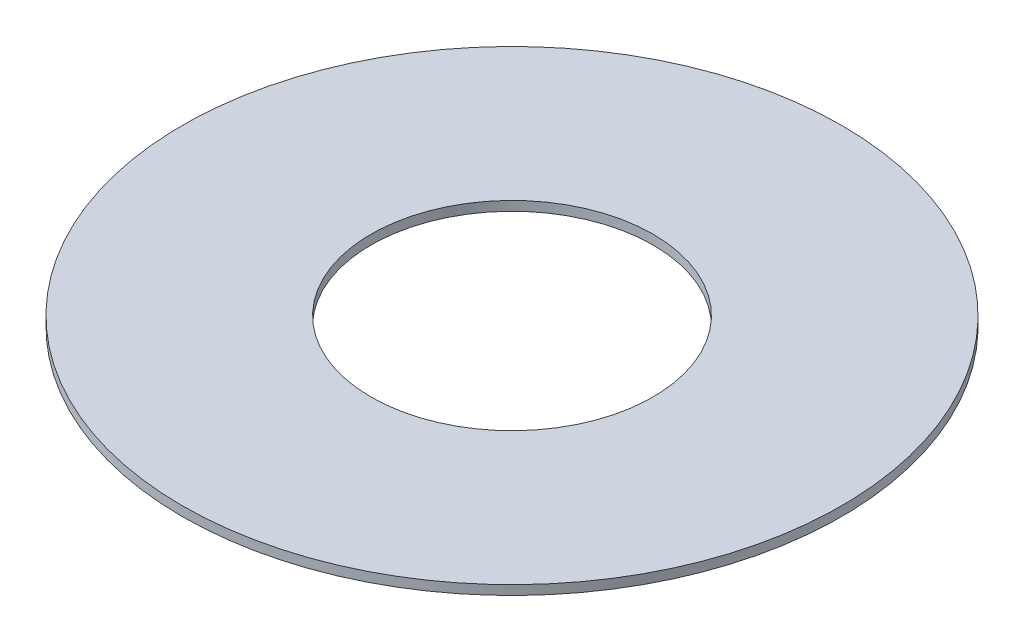
SolidWorks part; units mm, degrees
material "AISI 1045 钢，冷拔"
ref_plane "前视基准面" through (0, 0, 0) normal (0, 0, 1) x (1, 0, 0)
ref_plane "上视基准面" through (0, 0, 0) normal (0, 1, 0) x (1, 0, 0)
ref_plane "右视基准面" through (0, 0, 0) normal (1, 0, 0) x (0, 0, -1)
sketch "草图1" plane through (0, 0, 0) normal (0, 1, 0) x (1, 0, 0)
  circle A0 centre (0, 0) radius 1.5
  circle A1 centre (0, 0) radius 3.505
  dimension "D1" = 3
  dimension "D2" = 7.01
extrude "凸台-拉伸1" add sketch "草图1" along normal blind 0.1
